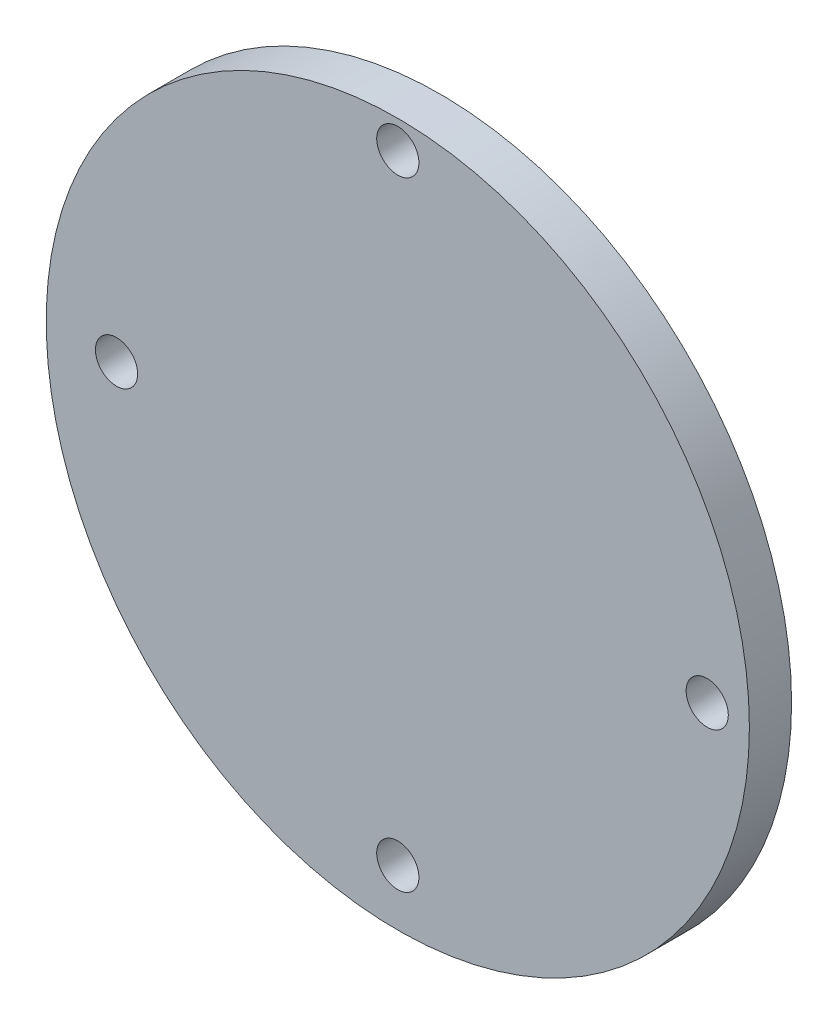
SolidWorks part; units mm, degrees
ref_plane "Płaszczyzna przednia" through (0, 0, 0) normal (0, 0, 1) x (1, 0, 0)
ref_plane "Płaszczyzna górna" through (0, 0, 0) normal (0, 1, 0) x (1, 0, 0)
ref_plane "Płaszczyzna prawa" through (0, 0, 0) normal (1, 0, 0) x (0, 0, -1)
sketch "Szkic1" plane through (0, 0, 0) normal (0, 0, 1) x (1, 0, 0)
  circle A0 centre (0, 0) radius 25
  dimension "D1" = 50
extrude "Dodanie-wyciągnięcie1" add sketch "Szkic1" along normal blind 3
sketch "Szkic2" plane through (0, 0, 0) normal (0, 0, -1) x (-1, 0, 0)
  circle A0 centre (0, 0) radius 5
  circle A1 centre (0, 0) radius 2.5
extrude "Dodanie-wyciągnięcie2" add sketch "Szkic2" along normal blind 12
sketch "Szkic3" plane through (0, 0, 0) normal (0, 1, 0) x (1, 0, 0)
  circle A0 centre (0, 6) radius 1.25
  point P2 (0, 0)
extrude "Wytnij-wyciągnięcie1" cut sketch "Szkic3" along normal up to next
sketch "Szkic4" plane through (0, 0, 3) normal (0, 0, 1) x (1, 0, 0)
  circle A0 centre (22, 0) radius 1.5
  circle A1 centre (-20, 0) radius 1.5
  circle A2 centre (0, -21) radius 1.5
  circle A3 centre (0, 23) radius 1.5
  point P8 (0, 0)
  point P9 (0, 0)
  point P10 (0, 0)
  point P11 (0, 0)
  dimension "D1" = 3
  dimension "D2" = 3
  dimension "D3" = 3
  dimension "D4" = 3
extrude "Wytnij-wyciągnięcie2" cut sketch "Szkic4" against normal up to next
